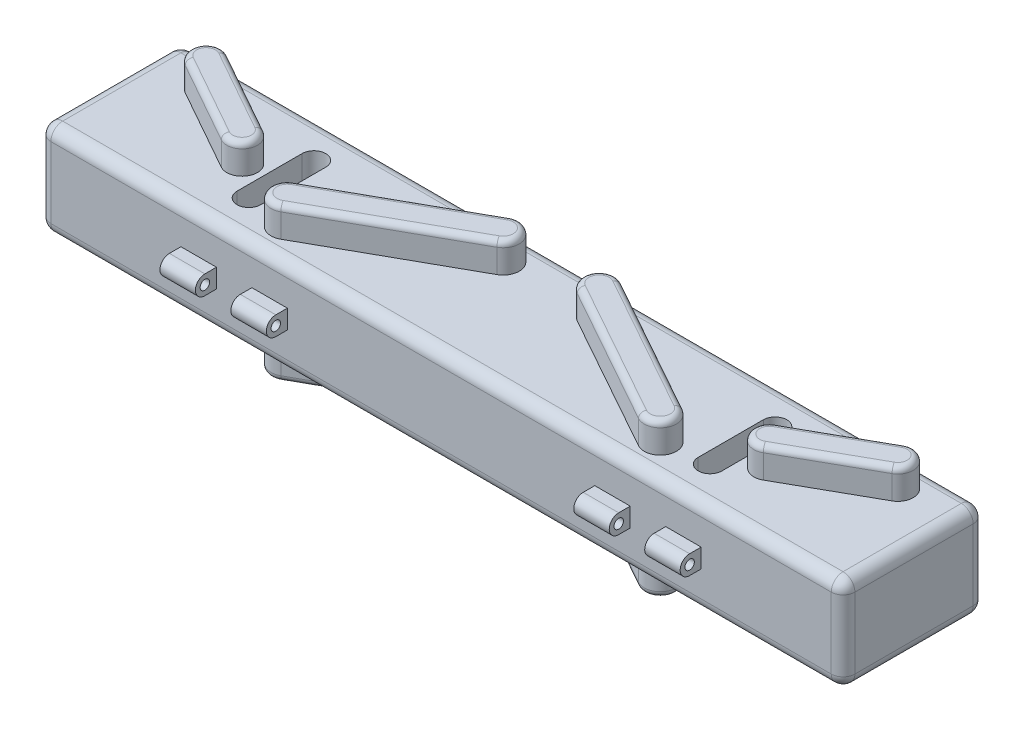
SolidWorks part; units mm, degrees
ref_plane "前视基准面" through (0, 0, 0) normal (0, 0, 1) x (1, 0, 0)
ref_plane "上视基准面" through (0, 0, 0) normal (0, 1, 0) x (1, 0, 0)
ref_plane "右视基准面" through (0, 0, 0) normal (1, 0, 0) x (0, 0, -1)
ref_plane "基准面4" through (-65, 0, 0) normal (1, 0, 0) x (0, 0, -1)
sketch "草图1" plane through (-65, 0, 0) normal (1, 0, 0) x (0, 0, -1)
  line L3 (-29.25, -148) -> (29.375, -148)
  line L4 (45.6548, -115.7072) -> (20.9133, -82.261)
  line L5 (8.4867, -80.7757) -> (-39.1877, -120.6049)
  line L6 (-29.25, -148) -> (29.375, -148)
  line L7 (45.6548, -115.7072) -> (20.9133, -82.261)
  line L8 (8.4867, -80.7757) -> (-39.1877, -120.6049)
  arc A3 (-39.1877, -120.6049) -> (-29.25, -148) centre (-29.25, -132.5) ccw
  arc A4 (29.375, -148) -> (45.6548, -115.7072) centre (29.375, -127.75) ccw
  arc A5 (20.9133, -82.261) -> (8.4867, -80.7757) centre (14, -87.375) ccw
  arc A6 (-39.1877, -120.6049) -> (-29.25, -148) centre (-29.25, -132.5) ccw
  arc A7 (29.375, -148) -> (45.6548, -115.7072) centre (29.375, -127.75) ccw
  arc A8 (20.9133, -82.261) -> (8.4867, -80.7757) centre (14, -87.375) ccw
  dimension "D1" = 0
sketch "草图2" plane through (-65, 0, 0) normal (1, 0, 0) x (0, 0, -1)
  line L3 (-29.25, -148) -> (29.375, -148)
  line L4 (45.6548, -115.7072) -> (20.9133, -82.261)
  line L5 (8.4867, -80.7757) -> (-39.1877, -120.6049)
  line L6 (-29.25, -148) -> (29.375, -148)
  line L7 (45.6548, -115.7072) -> (20.9133, -82.261)
  line L8 (8.4867, -80.7757) -> (-39.1877, -120.6049)
  circle A0 centre (1, -148) radius 3.488
  circle A1 centre (7.9761, -148) radius 3.488
  circle A2 centre (14.9521, -148) radius 3.488
  arc A3 (29.375, -148) -> (45.6548, -115.7072) centre (29.375, -127.75) ccw
  arc A4 (20.9133, -82.261) -> (8.4867, -80.7757) centre (14, -87.375) ccw
  arc A5 (-39.1877, -120.6049) -> (-29.25, -148) centre (-29.25, -132.5) ccw
  arc A6 (29.375, -148) -> (45.6548, -115.7072) centre (29.375, -127.75) ccw
  arc A7 (20.9133, -82.261) -> (8.4867, -80.7757) centre (14, -87.375) ccw
  arc A8 (-39.1877, -120.6049) -> (-29.25, -148) centre (-29.25, -132.5) ccw
  circle A9 centre (21.9282, -148) radius 3.488
  circle A10 centre (28.9043, -148) radius 3.488
  circle A11 centre (35.8014, -146.9532) radius 3.488
  circle A12 centre (41.9366, -143.6329) radius 3.488
  circle A13 centre (46.5811, -138.4277) radius 3.488
  circle A14 centre (49.1836, -131.9552) radius 3.488
  circle A15 centre (49.4352, -124.9837) radius 3.488
  circle A16 centre (47.3061, -118.3404) radius 3.488
  circle A17 centre (43.3515, -112.5935) radius 3.488
  circle A18 centre (39.2028, -106.9852) radius 3.488
  circle A19 centre (35.0541, -101.3768) radius 3.488
  circle A20 centre (30.9053, -95.7684) radius 3.488
  circle A21 centre (26.7566, -90.1601) radius 3.488
  circle A22 centre (22.6079, -84.5517) radius 3.488
  circle A23 centre (17.6875, -79.6065) radius 3.488
  circle A24 centre (10.7137, -79.4285) radius 3.488
  circle A25 centre (5.1161, -83.5917) radius 3.488
  circle A26 centre (-0.2375, -88.0643) radius 3.488
  circle A27 centre (-5.5912, -92.537) radius 3.488
  circle A28 centre (-10.9448, -97.0096) radius 3.488
  circle A29 centre (-16.2984, -101.4822) radius 3.488
  circle A30 centre (-21.652, -105.9549) radius 3.488
  circle A31 centre (-27.0056, -110.4275) radius 3.488
  circle A32 centre (-32.3592, -114.9001) radius 3.488
  circle A33 centre (-37.7128, -119.3728) radius 3.488
  circle A34 centre (-42.4961, -124.4507) radius 3.488
  circle A35 centre (-44.6843, -131.0747) radius 3.488
  circle A36 centre (-44.6843, -131.0747) radius 3.488
  circle A37 centre (-43.7461, -137.9874) radius 3.488
  circle A38 centre (-39.8716, -143.7886) radius 3.488
  circle A39 centre (-33.8455, -147.3031) radius 3.488
  circle A40 centre (-26.9043, -148) radius 3.488
  circle A41 centre (-19.9282, -148) radius 3.488
  circle A42 centre (-12.9521, -148) radius 3.488
  circle A43 centre (-5.9761, -148) radius 3.488
  dimension "D1" = 0
ref_plane "基准面5" through (0, -148, 0) normal (0, 1, 0) x (1, 0, 0)
sketch "草图3" plane through (0, -148, 0) normal (0, 1, 0) x (1, 0, 0)
  line L0 (-65, -29.25) -> (-65, 29.375) construction
  line L4 (-48, -5.488) -> (-82, -5.488)
  line L5 (-48, -5.488) -> (-48, 0.512)
  line L6 (-48, 0.512) -> (-82, 0.512)
  line L7 (-82, -5.488) -> (-82, 0.512)
  line L8 (-48, -5.488) -> (-82, 0.512) construction
  line L9 (-48, 0.512) -> (-82, -5.488) construction
  point P0 (-65, -2.488)
  point P6 (-65, -2.488)
  dimension "D1" = 34
  dimension "D2" = 6
extrude "凸台-拉伸1" add sketch "草图3" along normal mid plane 4
sketch "草图5" plane through (-65, 0, 0) normal (1, 0, 0) x (0, 0, -1)
  line L0 (0.512, -146) -> (0.512, -150) construction
  line L1 (0.512, -150) -> (-5.488, -150) construction
  line L2 (-5.488, -146) -> (-5.488, -150) construction
  line L3 (0.512, -146) -> (-5.488, -146) construction
  line L4 (0.512, -146) -> (0.512, -150)
  line L5 (0.512, -150) -> (-5.488, -150)
  line L6 (-5.488, -146) -> (-5.488, -150)
  line L7 (0.512, -146) -> (-5.488, -146)
  line L8 (-5.9761, -148) -> (1, -148) construction
  circle A0 centre (1, -148) radius 3.488 construction
  circle A1 centre (-5.9761, -148) radius 3.488 construction
  circle A2 centre (1, -148) radius 3.488
  circle A3 centre (-5.9761, -148) radius 3.488
  point P10 (-2.488, -148)
fillet "圆角1" radius 0.5 12 edges at (-48, -150, 2.488) (-48, -148, -0.512) (-65, -150, -0.512) (-65, -146, -0.512) (-48, -146, 2.488) (-65, -146, 5.488) (-48, -148, 5.488) (-65, -150, 5.488) (-82, -148, -0.512) (-82, -146, 2.488) (-82, -148, 5.488) (-82, -150, 2.488)
sketch "草图6" plane through (0, -150, 0) normal (0, -1, 0) x (1, 0, 0)
  line L0 (-65, 4.988) -> (-65, -0.012) construction
  line L1 (-48.5, 4.988) -> (-81.5, 4.988) construction
  line L2 (-81.5, -0.012) -> (-48.5, -0.012) construction
  line L3 (-74.75, 3.863) -> (-74.75, 1.113) construction
  line L4 (-74.25, 3.863) -> (-74.25, 1.113)
  line L5 (-75.25, 3.863) -> (-75.25, 1.113)
  line L6 (-74.75, 2.488) -> (-65, 2.488)
  line L7 (-55.25, 3.863) -> (-55.25, 1.113) construction
  line L8 (-55.75, 3.863) -> (-55.75, 1.113)
  line L9 (-54.75, 3.863) -> (-54.75, 1.113)
  arc A0 (-74.25, 3.863) -> (-75.25, 3.863) centre (-74.75, 3.863) ccw
  arc A1 (-75.25, 1.113) -> (-74.25, 1.113) centre (-74.75, 1.113) ccw
  arc A2 (-55.75, 3.863) -> (-54.75, 3.863) centre (-55.25, 3.863) cw
  arc A3 (-54.75, 1.113) -> (-55.75, 1.113) centre (-55.25, 1.113) cw
  point P8 (-74.75, 2.488)
  point P17 (-55.25, 2.488)
  dimension "D3" = 0.5
  dimension "D1" = 9.75
  dimension "D2" = 2.75
extrude "切除-拉伸1" cut sketch "草图6" against normal through all
sketch "草图7" plane through (0, -150, 0) normal (0, -1, 0) x (1, 0, 0)
  line L0 (-76.1435, 2.7569) -> (-79.6293, 0.7971) construction
  line L3 (-72.8909, 4.1075) -> (-67.0272, 0.8339) construction
  line L4 (-72.5601, 4.7001) -> (-66.6963, 1.4264)
  line L5 (-73.2217, 3.515) -> (-67.358, 0.2413)
  line L6 (-75.8266, 2.1932) -> (-79.3124, 0.2333)
  line L7 (-76.4605, 3.3206) -> (-79.9463, 1.3608)
  line L8 (-65, 11.5162) -> (-65, -3.3873) construction
  line L9 (-81.5, -0.012) -> (-48.5, -0.012)
  line L10 (-48.5, -0.012) -> (-48.5, 4.988)
  line L11 (-48.5, 4.988) -> (-81.5, 4.988)
  line L12 (-81.5, 4.988) -> (-81.5, -0.012)
  line L13 (-81.5, -0.012) -> (-48.5, -0.012)
  line L14 (-48.5, -0.012) -> (-48.5, 4.988)
  line L15 (-48.5, 4.988) -> (-81.5, 4.988)
  line L16 (-81.5, 4.988) -> (-81.5, -0.012)
  line L17 (-65, -8.4867) -> (-65, 39.1877) construction
  line L18 (-53.8565, 2.7569) -> (-50.3707, 0.7971) construction
  line L19 (-54.1734, 2.1932) -> (-50.6876, 0.2333)
  line L20 (-53.5395, 3.3206) -> (-50.0537, 1.3608)
  line L21 (-57.1091, 4.1075) -> (-62.9728, 0.8339) construction
  line L22 (-57.4399, 4.7001) -> (-63.3037, 1.4264)
  line L23 (-56.7783, 3.515) -> (-62.642, 0.2413)
  arc A2 (-72.5601, 4.7001) -> (-73.2217, 3.515) centre (-72.8909, 4.1075) ccw
  arc A3 (-67.358, 0.2413) -> (-66.6963, 1.4264) centre (-67.0272, 0.8339) ccw
  arc A4 (-75.8266, 2.1932) -> (-76.4605, 3.3206) centre (-76.1435, 2.7569) ccw
  arc A5 (-79.9463, 1.3608) -> (-79.3124, 0.2333) centre (-79.6293, 0.7971) ccw
  arc A6 (-54.1734, 2.1932) -> (-53.5395, 3.3206) centre (-53.8565, 2.7569) cw
  arc A7 (-50.0537, 1.3608) -> (-50.6876, 0.2333) centre (-50.3707, 0.7971) cw
  arc A8 (-57.4399, 4.7001) -> (-56.7783, 3.515) centre (-57.1091, 4.1075) cw
  arc A9 (-62.642, 0.2413) -> (-63.3037, 1.4264) centre (-62.9728, 0.8339) cw
  ellipse E0 centre (-65, 8.4707) end of major axis (-69.75, 8.4707) minor radius 3.0454 construction
  point P6 (-77.8864, 1.777)
  point P7 (-69.959, 2.4707)
  point P20 (-52.1136, 1.777)
  point P37 (-60.041, 2.4707)
  dimension "D1" = 0
extrude "凸台-拉伸2" add sketch "草图7" along normal blind 1.25 contours L5 A3 L4 A2 | L7 A5 L6 A4 | A9 L23 A8 L22 | A7 L20 A6 L19
fillet "圆角2" radius 0.25 16 edges at (-75.5798, -151.25, 3.0738) (-77.5695, -151.25, 1.2133) (-80.193, -151.25, 0.4801) (-78.2034, -151.25, 2.3407) (-73.4835, -151.25, 4.4383) (-69.6282, -151.25, 3.0632) (-66.4346, -151.25, 0.5031) (-70.2899, -151.25, 1.8782) (-52.4305, -151.25, 1.2133) (-54.4202, -151.25, 3.0738) (-51.7966, -151.25, 2.3407) (-49.807, -151.25, 0.4801) (-60.3718, -151.25, 3.0632) (-56.5165, -151.25, 4.4383) (-59.7101, -151.25, 1.8782) (-63.5654, -151.25, 0.5031)
ref_plane "基准面6" through (0, -148, 0) normal (0, -1, 0) x (-1, 0, 0)
mirror "镜向1" about plane through (0, -148, 0) normal (0, -1, 0) of "圆角2", "凸台-拉伸2"
sketch "草图8" plane through (-65, 0, 0) normal (1, 0, 0) x (0, 0, -1)
  line L0 (-2.488, -146.5) -> (-2.488, -149.5) construction
  line L1 (0.012, -146.5) -> (-4.988, -146.5) construction
  line L2 (-4.988, -149.5) -> (0.012, -149.5) construction
  line L3 (1, -148) -> (-5.9761, -148) construction
  line L4 (1, -148.4) -> (-5.9761, -148.4)
  line L5 (1, -147.6) -> (-5.9761, -147.6)
  arc A0 (1, -148.4) -> (1, -147.6) centre (1, -148) ccw
  arc A1 (-5.9761, -147.6) -> (-5.9761, -148.4) centre (-5.9761, -148) ccw
  circle A2 centre (1, -148) radius 0.2
  circle A3 centre (-5.9761, -148) radius 0.2
  point P8 (-2.488, -148)
  dimension "D1" = 0.4
  dimension "D2" = 0.4
  dimension "D3" = 0.4
extrude "凸台-拉伸3" add sketch "草图8" along normal mid plane 30
sketch "草图9" plane through (0, 0, 0) normal (0, 1, 0) x (1, 0, 0)
  line L0 (-65, -9.1986) -> (-65, 1.9291) construction
  line L1 (-65, -9.1986) -> (-65, 1.9291) construction
  line L7 (-76, 4.4427) -> (-76, -9.9117)
  line L8 (-77.5, 4.4427) -> (-52.5, 4.4427)
  line L9 (-77.5, 4.4427) -> (-77.5, -9.9117)
  line L10 (-77.5, -9.9117) -> (-52.5, -9.9117)
  line L11 (-52.5, 4.4427) -> (-52.5, -9.9117)
  line L12 (-77.5, 4.4427) -> (-52.5, -9.9117) construction
  line L13 (-77.5, -9.9117) -> (-52.5, 4.4427) construction
  line L14 (-74.5, 4.4427) -> (-74.5, -9.9117)
  line L15 (-73, 4.4427) -> (-73, -9.9117)
  line L16 (-71.5, 4.4427) -> (-71.5, -9.9117)
  line L17 (-54, 4.4427) -> (-54, -9.9117)
  line L18 (-55.5, 4.4427) -> (-55.5, -9.9117)
  line L19 (-57, 4.4427) -> (-57, -9.9117)
  line L20 (-58.5, 4.4427) -> (-58.5, -9.9117)
  line L21 (-80.5299, 0.512) -> (-80.5299, 2.9224)
  line L22 (-80.5299, 2.9224) -> (-77.5, 2.9224)
  line L23 (-80.5299, -5.488) -> (-80.5299, -7.8882)
  line L24 (-80.5299, -7.8882) -> (-77.5, -7.8882)
  line L25 (-82, -5.488) -> (-48, -5.488)
  line L26 (-82, 0.512) -> (-82, -5.488)
  line L27 (-48, 0.512) -> (-82, 0.512)
  line L28 (-48, -5.488) -> (-48, 0.512)
  line L29 (-82, -5.488) -> (-48, -5.488)
  line L30 (-82, 0.512) -> (-82, -5.488)
  line L31 (-48, 0.512) -> (-82, 0.512)
  line L32 (-48, -5.488) -> (-48, 0.512)
  line L33 (-52.5, 2.9224) -> (-49.7036, 2.9224)
  line L34 (-49.7036, 2.9224) -> (-49.7036, 0.512)
  line L35 (-49.7036, -5.488) -> (-49.7036, -7.8882)
  line L36 (-49.7036, -7.8882) -> (-52.5, -7.8882)
  point P2 (-65, -2.7345)
  dimension "D1" = 25
  dimension "D3" = 0
  dimension "D2" = 5
extrude "切除-拉伸2" cut sketch "草图9" against normal through all both and the other way through all contours L31 L9 L22 L21 | L31 L14 L8 L7 | L31 L16 L8 L15 | L31 L20 L8 L16 | L31 L19 L8 L20 | L31 L17 L8 L18 | L34 L33 L11 L31 | L36 L35 L29 L11 | L29 L17 L10 L11 | L29 L19 L10 L18 | L29 L16 L10 L20 | L29 L14 L10 L15 | L29 L9 L10 L7 | L29 L23 L24 L9
